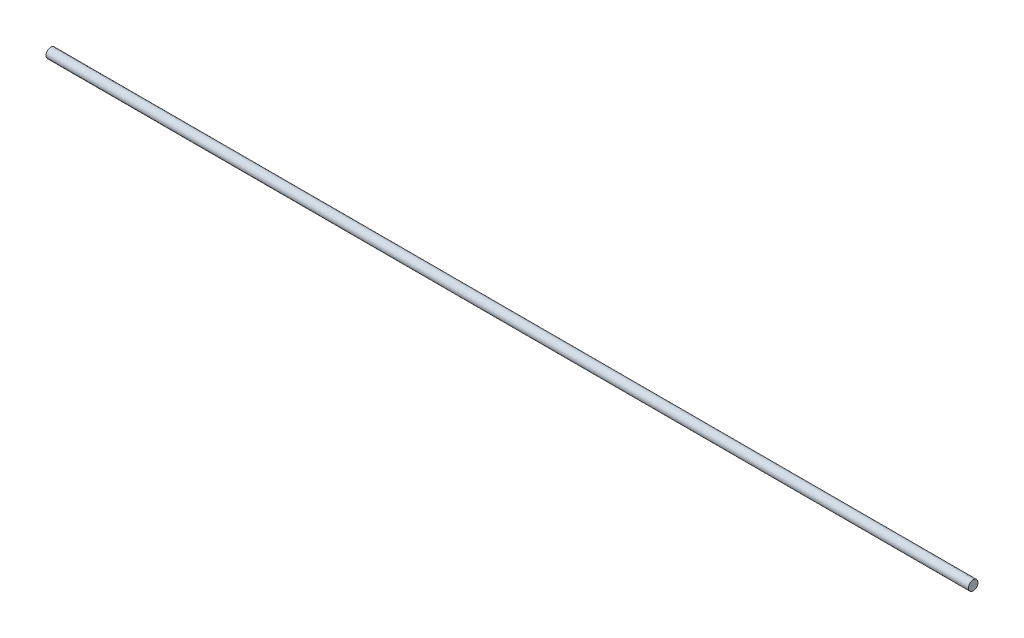
SolidWorks part; units mm, degrees
ref_plane "Front Plane" through (0, 0, 0) normal (0, 0, 1) x (1, 0, 0)
ref_plane "Top Plane" through (0, 0, 0) normal (0, 1, 0) x (1, 0, 0)
ref_plane "Right Plane" through (0, 0, 0) normal (1, 0, 0) x (0, 0, -1)
sketch "Sketch1" plane through (0, 0, 0) normal (1, 0, 0) x (0, 0, -1)
  circle A0 centre (0, 0) radius 1.5625
  dimension "D1" = 3.125
extrude "Boss-Extrude1" add sketch "Sketch1" along normal mid plane 300
